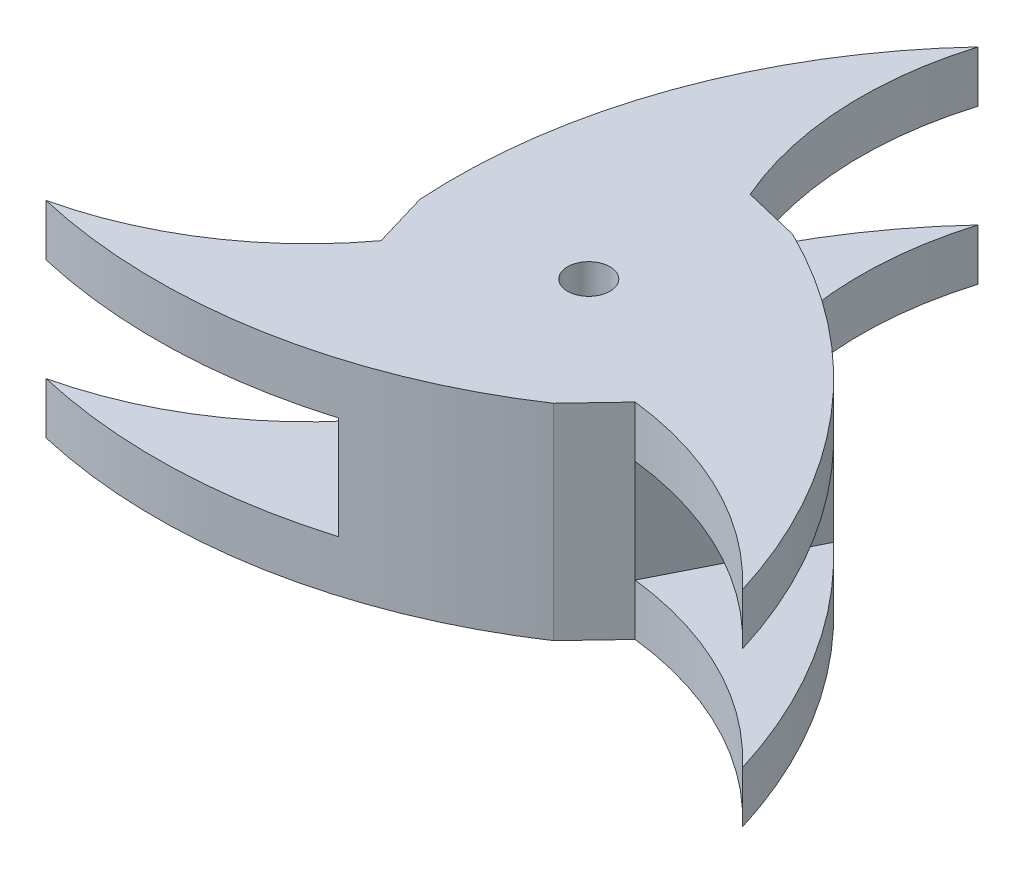
SolidWorks part; units mm, degrees
ref_plane "Front Plane" through (0, 0, 0) normal (0, 0, 1) x (1, 0, 0)
ref_plane "Top Plane" through (0, 0, 0) normal (0, 1, 0) x (1, 0, 0)
ref_plane "Right Plane" through (0, 0, 0) normal (1, 0, 0) x (0, 0, -1)
sketch "Sketch5" plane through (0, 0, 0) normal (0, 1, 0) x (1, 0, 0)
  line L4 (0.9069, 19.0284) -> (7.8299, 17.3665)
  line L5 (-16.9325, -8.7288) -> (-18.9548, -1.9024)
  line L6 (11.1249, -15.4641) -> (16.0256, -10.2996)
  arc A1 (-0.7905, 48.8751) -> (0.9069, 19.0284) centre (40.6308, 36.2591) ccw
  arc A3 (-0.7905, 48.8751) -> (-18.9548, -1.9024) centre (48.9349, 2.4495) ccw
  arc A13 (42.7223, -23.7529) -> (16.0256, -10.2996) centre (11.0859, -53.3169) ccw
  arc A14 (42.7223, -23.7529) -> (7.8299, 17.3665) centre (-22.3461, -43.6037) ccw
  arc A15 (-41.9318, -25.1221) -> (-16.9325, -8.7288) centre (-51.7167, 17.0578) ccw
  arc A16 (-41.9318, -25.1221) -> (11.1249, -15.4641) centre (-26.5888, 41.1541) ccw
  point P15 (0, 0)
  point P20 (0, 0)
  dimension "D1" = 3
  dimension "D4" = 43.3
  dimension "D5" = 68.0291
  dimension "D6" = 28.626
  dimension "D8" = 15.0964
  dimension "D9" = 6.8264
  dimension "D3" = 26.0272
  dimension "D7" = 31.1546
  dimension "D2" = 7.1197
extrude "Boss-Extrude2" add sketch "Sketch5" along normal blind 25.4
ref_plane "Plane1" through (1.9826, 0, -0.1128) normal (0.9984, 0, -0.0568) x (-0.0568, 0, -0.9984)
sketch "Sketch6" plane through (1.9826, 0, -0.1128) normal (0.9984, 0, -0.0568) x (-0.0568, 0, -0.9984)
  line L0 (48.8411, 25.4) -> (18.9462, 25.4) construction
  line L1 (48.8411, 25.4) -> (48.8411, 0) construction
  line L2 (48.8411, 19.05) -> (48.8411, 6.35)
  line L3 (48.8411, 19.05) -> (18.9462, 19.05)
  line L4 (18.9462, 25.4) -> (18.9462, 0) construction
  line L5 (18.9462, 19.05) -> (18.9462, 6.35)
  line L6 (18.9462, 6.35) -> (48.8411, 6.35)
  dimension "D1" = 12.7
  dimension "D2" = 6.35
extrude "Cut-Extrude2" cut sketch "Sketch6" against normal blind 25.4
ref_plane "Plane2" through (-0.8937, 0, 1.7734) normal (-0.45, 0, 0.893) x (0.893, 0, 0.45)
sketch "Sketch7" plane through (-0.8937, 0, 1.7734) normal (-0.45, 0, 0.893) x (0.893, 0, 0.45)
  line L1 (48.8411, 25.4) -> (48.8411, 0) construction
  line L2 (48.8411, 6.35) -> (48.8411, 19.05)
  line L3 (48.8411, 6.35) -> (18.9462, 6.35)
  line L4 (18.9462, 25.4) -> (18.9462, 0) construction
  line L5 (18.9462, 6.35) -> (18.9462, 19.05)
  line L6 (18.9462, 19.05) -> (48.8411, 19.05)
  line L7 (48.8411, 25.4) -> (18.9462, 25.4) construction
  dimension "D1" = 12.7
  dimension "D2" = 6.35
extrude "Cut-Extrude3" cut sketch "Sketch7" against normal blind 25.4
ref_plane "Plane3" through (-1.089, 0, -1.6606) normal (-0.5484, 0, -0.8362) x (-0.8362, 0, 0.5484)
sketch "Sketch8" plane through (-1.089, 0, -1.6606) normal (-0.5484, 0, -0.8362) x (-0.8362, 0, 0.5484)
  line L1 (48.8411, 25.4) -> (48.8411, 0) construction
  line L2 (48.8411, 6.35) -> (48.8411, 19.05)
  line L3 (48.8411, 19.05) -> (18.9462, 19.05)
  line L4 (18.9462, 25.4) -> (18.9462, 0) construction
  line L5 (18.9462, 19.05) -> (18.9462, 6.35)
  line L6 (18.9462, 6.35) -> (48.8411, 6.35)
  line L7 (48.8411, 25.4) -> (18.9462, 25.4) construction
  dimension "D1" = 12.7
  dimension "D2" = 6.35
extrude "Cut-Extrude4" cut sketch "Sketch8" against normal blind 25.4
sketch "Sketch9" plane through (0, 0, 0) normal (0, 1, 0) x (1, 0, 0)
  circle A0 centre (0, 0) radius 2.626
extrude "Cut-Extrude5" cut sketch "Sketch9" along normal blind 25.4
